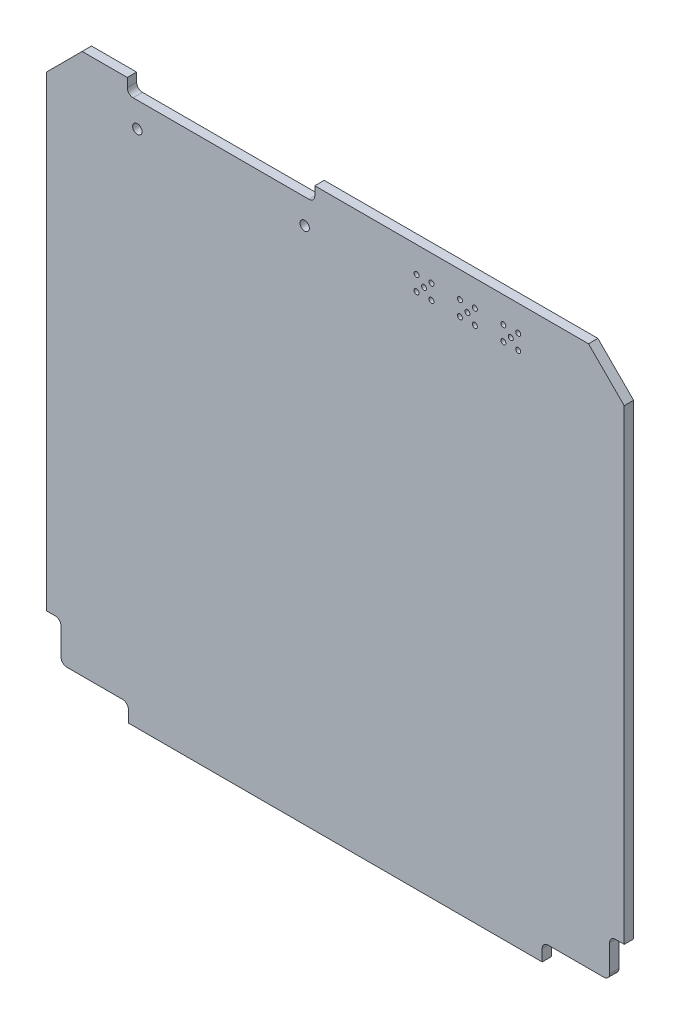
SolidWorks part; units mm, degrees
ref_plane "Front Plane" through (0, 0, 0) normal (0, 0, 1) x (1, 0, 0)
ref_plane "Top Plane" through (0, 0, 0) normal (0, 1, 0) x (1, 0, 0)
ref_plane "Right Plane" through (0, 0, 0) normal (1, 0, 0) x (0, 0, -1)
ref_plane "Plane4" through (0, 0, -0.0125) normal (0, 0, -1) x (-1, 0, 0)
sketch "Sketch1" plane through (0, 0, -0.0125) normal (0, 0, -1) x (-1, 0, 0)
  line L0 (35.3, -50) -> (35.3, -48)
  line L1 (36.3, -47) -> (45.8, -47)
  line L2 (46.8, -46) -> (46.8, -41.4)
  line L3 (47.8, -40.4) -> (49.3, -40.4)
  line L4 (49.3, -40.4) -> (49.3, 39.2)
  line L5 (49.3, 39.2) -> (43.2, 45.3)
  line L6 (43.2, 45.3) -> (35.5, 45.3)
  line L7 (35.5, 45.3) -> (35.5, 43.8)
  line L8 (34.5, 42.8) -> (4.5, 42.8)
  line L9 (3.5, 43.8) -> (3.5, 45.3)
  line L10 (3.5, 45.3) -> (-43.2, 45.3)
  line L11 (-43.2, 45.3) -> (-49.3, 39.2)
  line L12 (-49.3, 39.2) -> (-49.3, -40.4)
  line L13 (-49.3, -40.4) -> (-47.8, -40.4)
  line L14 (-46.8, -41.4) -> (-46.8, -46)
  line L15 (-45.8, -47) -> (-36.3, -47)
  line L16 (-35.3, -48) -> (-35.3, -50)
  line L17 (-35.3, -50) -> (35.3, -50)
  line L18 (0, -50) -> (0, 45.3) construction
  line L19 (19.5, 42.8) -> (19.5, 25.5258) construction
  line L20 (-13.87, 40.87) -> (-16.41, 38.33) construction
  line L21 (-21.27, 40.87) -> (-23.81, 38.33) construction
  line L22 (-28.67, 40.87) -> (-31.21, 38.33) construction
  arc A0 (35.3, -48) -> (36.3, -47) centre (36.3, -48) cw
  arc A1 (45.8, -47) -> (46.8, -46) centre (45.8, -46) ccw
  arc A2 (46.8, -41.4) -> (47.8, -40.4) centre (47.8, -41.4) cw
  arc A3 (35.5, 43.8) -> (34.5, 42.8) centre (34.5, 43.8) cw
  arc A4 (4.5, 42.8) -> (3.5, 43.8) centre (4.5, 43.8) cw
  arc A5 (-47.8, -40.4) -> (-46.8, -41.4) centre (-47.8, -41.4) cw
  arc A6 (-46.8, -46) -> (-45.8, -47) centre (-45.8, -46) ccw
  arc A7 (-36.3, -47) -> (-35.3, -48) centre (-36.3, -48) cw
  circle A8 centre (-21.27, 40.87) radius 0.425
  circle A9 centre (-23.81, 40.87) radius 0.425
  circle A10 centre (-22.54, 39.6) radius 0.425
  circle A11 centre (-13.87, 40.87) radius 0.425
  circle A12 centre (-23.81, 38.33) radius 0.425
  circle A13 centre (-16.41, 40.87) radius 0.425
  circle A14 centre (-15.14, 39.6) radius 0.425
  circle A15 centre (-21.27, 38.33) radius 0.425
  circle A16 centre (-28.67, 40.87) radius 0.425
  circle A17 centre (-31.21, 40.87) radius 0.425
  circle A18 centre (-16.41, 38.33) radius 0.425
  circle A19 centre (-29.94, 39.6) radius 0.425
  circle A20 centre (-31.21, 38.33) radius 0.425
  circle A21 centre (-28.67, 38.33) radius 0.425
  circle A22 centre (33.775, 38.54) radius 0.8
  circle A23 centre (5.225, 38.54) radius 0.8
  circle A24 centre (-13.87, 38.33) radius 0.425
  point P35 (-15.14, 39.6)
  dimension "D7" = 2.5
  dimension "D8" = 1.6
  dimension "D9" = 14.275
  dimension "D10" = 4.26
  dimension "D11" = 1
  dimension "D12" = 1
  dimension "D13" = 1
  dimension "D14" = 1
  dimension "D15" = 1
  dimension "D16" = 1
  dimension "D17" = 1
  dimension "D18" = 1
  dimension "D26" = 0.85
  dimension "D1" = 98.6
  dimension "D2" = 95.3
  dimension "D3" = 14
  dimension "D4" = 9.6
  dimension "D5" = 2.5
  dimension "D6" = 3
  dimension "D19" = 14
  dimension "D20" = 2.5
  dimension "D21" = 6.1
  dimension "D22" = 6.1
  dimension "D23" = 32
  dimension "D24" = 2.54
  dimension "D25" = 2.54
  dimension "D28" = 7.4
  dimension "D29" = 4.43
  dimension "D30" = 35.43
  dimension "D31" = 45
  dimension "D32" = 45
  dimension "D33" = 29.8
  dimension "D34" = 50
  dimension "D27" = 3
extrude "Boss-Extrude1" add sketch "Sketch1" against normal blind 1.6
sketch "thermalContacts" plane through (0, 0, -0.0125) normal (0, 0, -1) x (-1, 0, 0)
  line L0 (-47, 35.5) -> (-47, -41.5) construction
  line L1 (-41.5, 35.5) -> (-41.5, 41.5) construction
  line L2 (-41.5, 35.5) -> (-47, 35.5) construction
  line L3 (-47, 35.5) -> (-47, -41.5)
  line L4 (-41.5, 35.5) -> (-41.5, 41.5)
  line L5 (-41.5, 35.5) -> (-47, 35.5)
  line L6 (47, 35.5) -> (47, -41.5) construction
  line L7 (41.5, 35.5) -> (47, 35.5) construction
  line L8 (41.5, 35.5) -> (41.5, 41.5) construction
  line L9 (47, 35.5) -> (47, -41.5)
  line L10 (41.5, 35.5) -> (47, 35.5)
  line L11 (41.5, 35.5) -> (41.5, 41.5)
  line L12 (41.5, 41.5) -> (41.5, 47) construction
  line L13 (41.5, 41.5) -> (49.5, 41.5) construction
  line L14 (41.5, 41.5) -> (41.5, 47)
  line L15 (41.5, 41.5) -> (49.5, 41.5)
  line L16 (-41.5, 41.5) -> (-41.5, 47) construction
  line L17 (-41.5, 41.5) -> (-49.5, 41.5) construction
  line L18 (-41.5, 41.5) -> (-41.5, 47)
  line L19 (-41.5, 41.5) -> (-49.5, 41.5)
